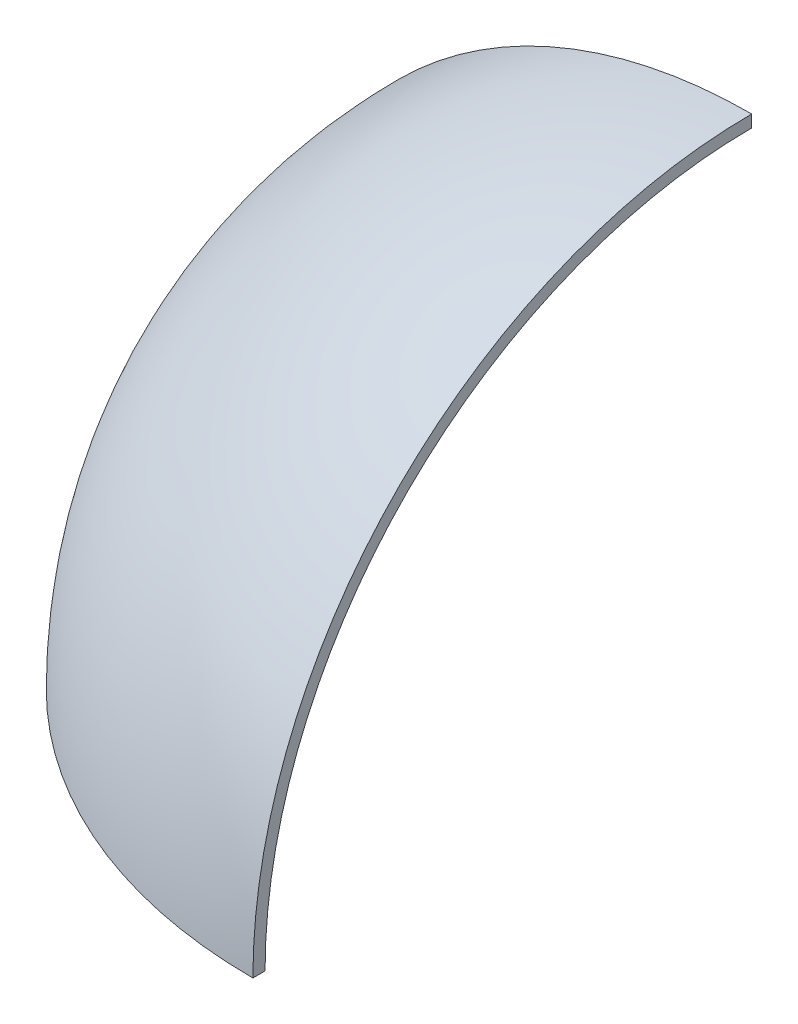
SolidWorks part; units mm, degrees
ref_plane "前视基准面" through (0, 0, 0) normal (0, 0, 1) x (1, 0, 0)
ref_plane "上视基准面" through (0, 0, 0) normal (0, 1, 0) x (1, 0, 0)
ref_plane "右视基准面" through (0, 0, 0) normal (1, 0, 0) x (0, 0, -1)
sketch "草图2" plane through (0, 0, 0) normal (0, 0, 1) x (1, 0, 0)
  line L4 (0, 40) -> (0, 41)
  line L5 (-40, 0) -> (-41, 0)
  line L7 (0, 0) -> (-40, 0) construction
  line L8 (0, 0) -> (0, 40) construction
  line L9 (1, -1) -> (1, 40.9878) construction
  line L10 (1, -1) -> (-40.9878, -1) construction
  arc A0 (0, 40) -> (-40, 0) centre (0, 0) ccw
  arc A1 (0, 41) -> (-41, 0) centre (0, 0) ccw
  arc A3 (1, 40.9878) -> (-40.9878, -1) centre (0, 0) ccw construction
  dimension "D1" = 40
  dimension "D2" = 1
revolve "旋转1" add sketch "草图2" angle 90 about L4
